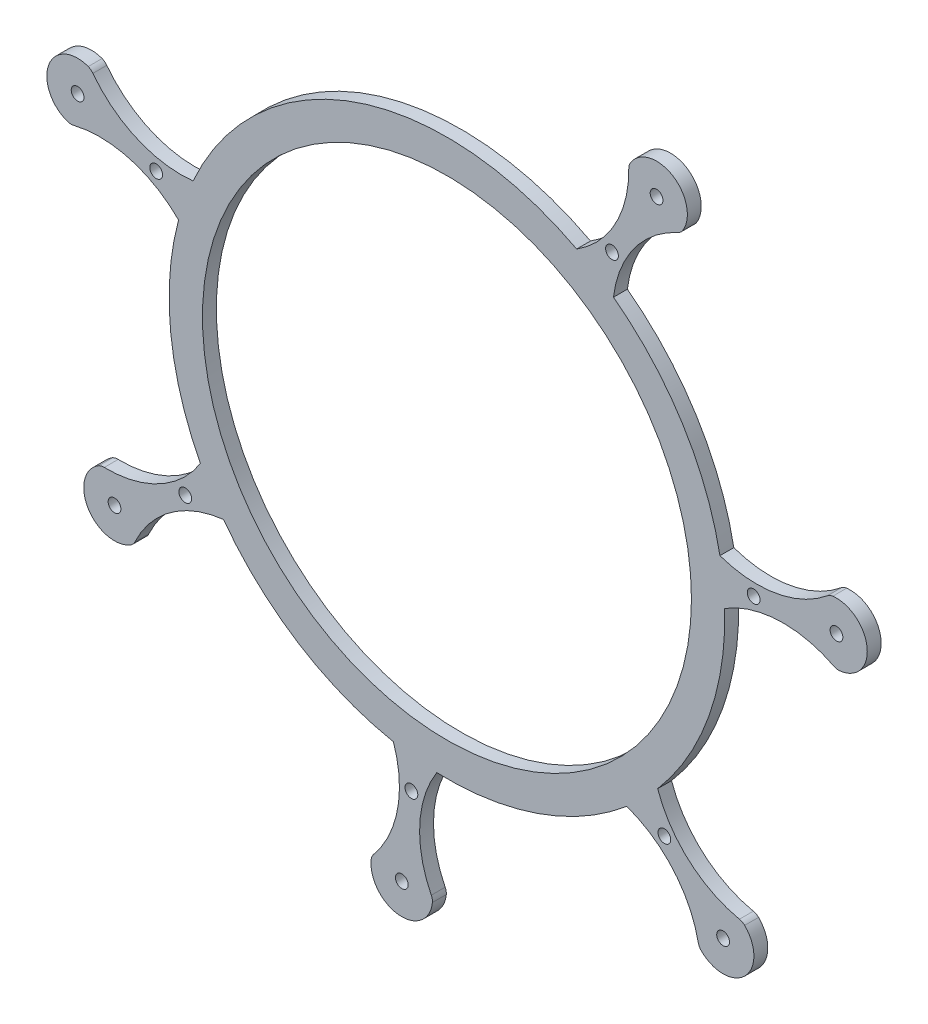
SolidWorks part; units mm, degrees
ref_plane "Front Plane" through (0, 0, 0) normal (0, 0, 1) x (1, 0, 0)
ref_plane "Top Plane" through (0, 0, 0) normal (0, 1, 0) x (1, 0, 0)
ref_plane "Right Plane" through (0, 0, 0) normal (1, 0, 0) x (0, 0, -1)
sketch "Sketch1" plane through (0, 0, 0) normal (0, 0, 1) x (1, 0, 0)
  circle A0 centre (-10.3254, -88.9588) radius 1.4605
  circle A1 centre (-8.1296, -70.0357) radius 1.4605
  circle A14 centre (-75.9795, -47.3922) radius 1.4605
  circle A15 centre (-59.8158, -37.3106) radius 1.4605
  circle A16 centre (-84.4161, 29.8546) radius 1.4605
  circle A17 centre (-66.4562, 23.5031) radius 1.4605
  circle A18 centre (-29.2823, 84.6132) radius 1.4605
  circle A19 centre (-23.0503, 66.6114) radius 1.4605
  circle A20 centre (47.9051, 75.6493) radius 1.4605
  circle A21 centre (37.7163, 59.5529) radius 1.4605
  circle A22 centre (89.0223, 9.7128) radius 1.4605
  circle A23 centre (70.0851, 7.6428) radius 1.4605
  circle A24 centre (63.1073, -63.5446) radius 1.4605
  circle A25 centre (49.6818, -50.0296) radius 1.4605
  arc A41 (88.3712, 2.9921) -> (63.4667, 1.9221) centre (76.869, -19.6543) ccw
  arc A42 (89.698, 2.7095) -> (88.1676, 16.6965) centre (89.0223, 9.7128) ccw
  arc A43 (88.1676, 16.6965) -> (86.9295, 16.1681) centre (88.5099, 14.1797) ccw
  arc A44 (62.3829, 11.8273) -> (86.9295, 16.1681) centre (70.8022, 35.7913) ccw
  arc A45 (88.3712, 2.9921) -> (89.698, 2.7095) centre (89.5445, 5.2449) ccw
  arc A46 (48.1491, -41.4059) -> (63.4667, 1.9221) centre (-0.0039, -0.0109) ccw
  arc A47 (48.1491, -41.4059) -> (66.8393, -57.8989) centre (72.138, -33.0577) ccw
  arc A48 (57.445, -67.233) -> (41.0807, -48.429) centre (32.5678, -72.36) ccw
  arc A49 (68.0345, -58.5221) -> (66.8393, -57.8989) centre (66.3046, -60.382) ccw
  arc A50 (58.0532, -68.4394) -> (68.0345, -58.5221) centre (63.1073, -63.5446) ccw
  arc A51 (57.445, -67.233) -> (58.0532, -68.4394) centre (59.9354, -66.7338) ccw
  arc A52 (-2.3448, -63.4678) -> (41.0807, -48.429) centre (-0.0039, -0.0109) ccw
  arc A53 (-2.3448, -63.4678) -> (-3.5861, -88.3618) centre (19.1395, -77.017) ccw
  arc A54 (-16.7411, -86.8367) -> (-12.2425, -62.3185) centre (-36.2602, -70.5836) ccw
  arc A55 (-16.7411, -86.8367) -> (-17.3034, -88.0591) centre (-14.7972, -88.4716) ccw
  arc A56 (-17.3034, -88.0591) -> (-3.3266, -89.6795) centre (-10.3254, -88.9588) ccw
  arc A57 (-3.3266, -89.6795) -> (-3.5861, -88.3618) centre (-5.8598, -89.494) ccw
  arc A58 (-51.0813, -37.7351) -> (-12.2425, -62.3185) centre (-0.0039, -0.0109) ccw
  arc A59 (-51.0813, -37.7351) -> (-71.3136, -52.2965) centre (-48.2692, -62.979) ccw
  arc A60 (-72.1793, -53.3134) -> (-71.3136, -52.2965) centre (-73.6126, -51.2164) ccw
  arc A61 (-79.6269, -41.3756) -> (-72.1793, -53.3134) centre (-75.9795, -47.3922) ccw
  arc A62 (-78.3233, -41.0607) -> (-79.6269, -41.3756) centre (-78.3998, -43.5995) ccw
  arc A63 (-78.3233, -41.0607) -> (-56.3494, -29.2909) centre (-77.786, -15.6664) ccw
  arc A64 (-61.3449, 16.4028) -> (-56.3494, -29.2909) centre (-0.0039, -0.0109) ccw
  arc A65 (-61.3449, 16.4028) -> (-85.3441, 23.1422) centre (-79.3281, -1.5351) ccw
  arc A66 (-81.9863, 36.4575) -> (-86.6761, 23.1917) centre (-84.4161, 29.8546) ccw
  arc A67 (-86.6761, 23.1917) -> (-85.3441, 23.1422) centre (-85.9191, 25.6162) ccw
  arc A68 (-80.93, 35.6279) -> (-81.9863, 36.4575) centre (-82.9712, 34.1162) ccw
  arc A69 (-80.93, 35.6279) -> (-58.0276, 25.7863) centre (-60.741, 51.041) ccw
  arc A70 (-25.4237, 58.1883) -> (-35.1179, 81.1536) centre (-50.6604, 61.0641) ccw
  arc A71 (29.6382, 56.146) -> (-58.0276, 25.7863) centre (-0.0039, -0.0109) ccw
  arc A72 (-22.605, 86.8303) -> (-35.9007, 82.2259) centre (-29.2823, 84.6132) ccw
  arc A73 (-35.9007, 82.2259) -> (-35.1179, 81.1536) centre (-33.5291, 83.1353) ccw
  arc A74 (-22.604, 85.4873) -> (-22.605, 86.8303) centre (-25.0541, 86.1571) ccw
  arc A75 (-22.604, 85.4873) -> (-16.019, 61.4453) centre (2.0341, 79.3128) ccw
  arc A76 (29.6382, 56.146) -> (41.5489, 78.0438) centre (16.1517, 77.6698) ccw
  arc A77 (53.8018, 71.8111) -> (41.9121, 79.3352) centre (47.9051, 75.6493) ccw
  arc A78 (41.9121, 79.3352) -> (41.5489, 78.0438) centre (44.0889, 78.0263) ccw
  arc A79 (52.7394, 70.9621) -> (53.8018, 71.8111) centre (51.7427, 73.2983) ccw
  arc A80 (52.7394, 70.9621) -> (38.0581, 50.8176) centre (63.2847, 47.8545) ccw
  arc A81 (62.3829, 11.8273) -> (38.0581, 50.8176) centre (-0.0039, -0.0109) ccw
  circle A82 centre (-0.0039, -0.0109) radius 55.88
  point P109 (0, 0)
  point P139 (0.0045, -0.0094)
  dimension "D1" = 7
  dimension "D3" = 7.0358
  dimension "D2" = 7.0358
  dimension "D4" = 7.0358
  dimension "D5" = 7.0358
  dimension "D6" = 7.0358
  dimension "D7" = 7.0358
  dimension "D8" = 7.0358
  dimension "D9" = 2.921
extrude "Boss-Extrude1" add sketch "Sketch1" along normal blind 3.175 contours A44 A81 A80 A79 A77 A78 A76 A71 A69 A68 A66 A67 A65 A64 A63 A62 A61 A60 A59 A58 A54 A55 A56 A57 A53 A52 A48 A51 A50 A49 A47 A46 A41 A45 A42 A43 A82
sketch "Sketch2" plane through (0, 0, 0) normal (0, 0, -1) x (-1, 0, 0)
  line L0 (91.0496, 32.1997) -> (0, 0) construction
  arc A0 (86.6761, 23.1917) -> (81.9863, 36.4575) centre (84.4161, 29.8546) ccw construction
